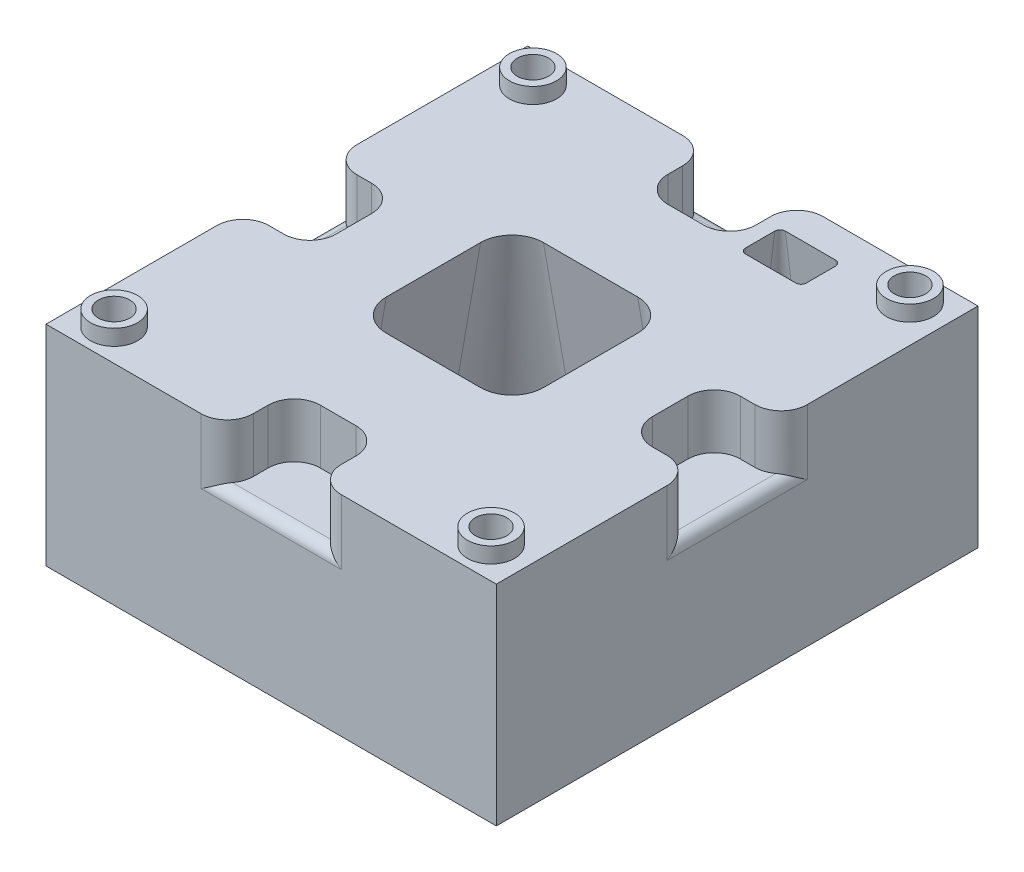
SolidWorks part; units mm, degrees
ref_plane "Plan de face" through (0, 0, 0) normal (0, 0, 1) x (1, 0, 0)
ref_plane "Plan de dessus" through (0, 0, 0) normal (0, 1, 0) x (1, 0, 0)
ref_plane "Plan de droite" through (0, 0, 0) normal (1, 0, 0) x (0, 0, -1)
sketch "Esquisse1" plane through (0, 0, 0) normal (0, 1, 0) x (1, 0, 0)
  line L0 (-19, 4.2) -> (-17.6, 4.2)
  line L1 (-19, 23) -> (-6.7, 23)
  line L2 (-21.5, 20.5) -> (-21.5, 6.7)
  line L3 (-19, -23) -> (-6.7, -23)
  line L4 (21.5, 20.5) -> (21.5, 6.7)
  line L5 (-21.5, 23) -> (21.5, -23) construction
  line L6 (-21.5, -23) -> (21.5, 23) construction
  line L7 (-15.1, 1.7) -> (-15.1, -1.7)
  line L8 (-17.6, -4.2) -> (-19, -4.2)
  line L9 (-4.2, 20.5) -> (-4.2, 19.1)
  line L10 (-1.7, 16.6) -> (1.7, 16.6)
  line L11 (4.2, 19.1) -> (4.2, 20.5)
  line L12 (19, 4.2) -> (17.6, 4.2)
  line L13 (15.1, 1.7) -> (15.1, -1.7)
  line L14 (17.6, -4.2) -> (19, -4.2)
  line L15 (-4.2, -20.5) -> (-4.2, -19.1)
  line L16 (-1.7, -16.6) -> (1.7, -16.6)
  line L17 (4.2, -19.1) -> (4.2, -20.5)
  line L18 (6.7, 23) -> (19, 23)
  line L19 (21.5, -6.7) -> (21.5, -20.5)
  line L20 (6.7, -23) -> (19, -23)
  line L21 (-21.5, -6.7) -> (-21.5, -20.5)
  line L22 (-21.5, -20.5) -> (-21.5, -23)
  line L23 (-21.5, -23) -> (-19, -23)
  line L24 (19, -23) -> (21.5, -23)
  line L25 (21.5, -23) -> (21.5, -20.5)
  line L26 (19, 23) -> (21.5, 23)
  line L27 (21.5, 23) -> (21.5, 20.5)
  line L28 (-19, 23) -> (-21.5, 23)
  line L29 (-21.5, 23) -> (-21.5, 20.5)
  circle A0 centre (-18, 20) radius 1.5
  circle A1 centre (18, 20) radius 1.5
  circle A2 centre (18, -20) radius 1.5
  circle A3 centre (-18, -20) radius 1.5
  arc A4 (19, 4.2) -> (21.5, 6.7) centre (19, 6.7) ccw
  arc A6 (6.7, 23) -> (4.2, 20.5) centre (6.7, 20.5) ccw
  arc A7 (-4.2, 20.5) -> (-6.7, 23) centre (-6.7, 20.5) ccw
  arc A9 (-21.5, 6.7) -> (-19, 4.2) centre (-19, 6.7) ccw
  arc A10 (-19, -4.2) -> (-21.5, -6.7) centre (-19, -6.7) ccw
  arc A12 (-4.2, -20.5) -> (-6.7, -23) centre (-6.7, -20.5) cw
  arc A13 (4.2, -20.5) -> (6.7, -23) centre (6.7, -20.5) ccw
  arc A15 (21.5, -6.7) -> (19, -4.2) centre (19, -6.7) ccw
  arc A16 (4.2, 19.1) -> (1.7, 16.6) centre (1.7, 19.1) cw
  arc A17 (-1.7, 16.6) -> (-4.2, 19.1) centre (-1.7, 19.1) cw
  arc A18 (-17.6, 4.2) -> (-15.1, 1.7) centre (-17.6, 1.7) cw
  arc A19 (-15.1, -1.7) -> (-17.6, -4.2) centre (-17.6, -1.7) cw
  arc A20 (15.1, 1.7) -> (17.6, 4.2) centre (17.6, 1.7) cw
  arc A21 (15.1, -1.7) -> (17.6, -4.2) centre (17.6, -1.7) ccw
  arc A22 (4.2, -19.1) -> (1.7, -16.6) centre (1.7, -19.1) ccw
  arc A23 (-1.7, -16.6) -> (-4.2, -19.1) centre (-1.7, -19.1) ccw
  point P0 (0, 0)
  point P37 (4.2, 23)
  point P40 (-4.2, 23)
  point P46 (-21.5, 4.2)
  point P49 (-21.5, -4.2)
  point P55 (-4.2, -23)
  point P58 (4.2, -23)
  point P64 (21.5, -4.2)
  point P69 (-4.2, 16.6)
  point P72 (-15.1, 4.2)
  point P75 (-15.1, -4.2)
  point P80 (15.1, -4.2)
  point P83 (4.2, -16.6)
  dimension "D3" = 3
  dimension "D4" = 3
  dimension "D5" = 3
  dimension "D6" = 3
  dimension "D21" = 2.5
  dimension "D1" = 46
  dimension "D2" = 43
  dimension "D7" = 36
  dimension "D8" = 36
  dimension "D9" = 17.3
  dimension "D10" = 17.3
  dimension "D11" = 6.4
  dimension "D12" = 18.8
  dimension "D13" = 18.8
  dimension "D14" = 6.4
  dimension "D15" = 6.4
  dimension "D16" = 18.8
  dimension "D17" = 18.8
  dimension "D18" = 17.3
  dimension "D19" = 17.3
  dimension "D20" = 6.4
  dimension "D22" = 3.5
  dimension "D23" = 3
  dimension "D24" = 3.5
  dimension "D25" = 3
extrude "Boss.-Extru.1" add sketch "Esquisse1" along normal blind 20
sketch "Esquisse2" plane through (0, 20, 0) normal (0, 1, 0) x (1, 0, 0)
  circle A0 centre (-18, 20) radius 2.25
  circle A2 centre (18, 20) radius 2.25
  circle A3 centre (18, -20) radius 2.25
  circle A4 centre (-18, -20) radius 2.25
  circle A5 centre (-18, 20) radius 1.5 construction
  circle A6 centre (18, 20) radius 1.5 construction
  circle A7 centre (18, -20) radius 1.5 construction
  circle A8 centre (-18, -20) radius 1.5 construction
  circle A9 centre (-18, 20) radius 1.5
  circle A10 centre (18, 20) radius 1.5
  circle A11 centre (18, -20) radius 1.5
  circle A12 centre (-18, -20) radius 1.5
  dimension "D1" = 4.5
  dimension "D2" = 4.5
  dimension "D3" = 4.5
  dimension "D4" = 4.5
extrude "Boss.-Extru.2" add sketch "Esquisse2" along normal blind 1.5
sketch "Esquisse6" plane through (0, 0, 0) normal (0, -1, 0) x (1, 0, 0)
  line L0 (-21.5, 6.7) -> (-21.5, 23) construction
  line L1 (-21.5, 9.5229) -> (-14.2843, 9.5229)
  line L2 (-21.5, 9.5229) -> (-21.5, -8.8427)
  line L3 (-21.5, -8.8427) -> (-14.2843, -8.8427)
  line L4 (-14.2843, 9.5229) -> (-14.2843, -8.8427)
  line L5 (-21.5, 23) -> (-6.7, 23) construction
  line L6 (-8.3892, 23) -> (7.4067, 23)
  line L7 (-8.3892, 23) -> (-8.3892, 15.8715)
  line L8 (-8.3892, 15.8715) -> (7.4067, 15.8715)
  line L9 (7.4067, 23) -> (7.4067, 15.8715)
  line L10 (21.5, 23) -> (21.5, 6.7) construction
  line L11 (21.5, 11.3368) -> (14.511, 11.3368)
  line L12 (21.5, 11.3368) -> (21.5, -8.8427)
  line L13 (21.5, -8.8427) -> (14.511, -8.8427)
  line L14 (14.511, 11.3368) -> (14.511, -8.8427)
  line L15 (-4.2, -19.1) -> (-4.2, -20.5) construction
  line L16 (-4.2, -19.1) -> (-4.2, -20.5)
  line L17 (-6.7, -23) -> (8.6915, -23)
  line L18 (21.5, -23) -> (6.7, -23) construction
  line L19 (8.6915, -23) -> (8.6915, -16.6)
  line L20 (8.6915, -16.6) -> (-1.7, -16.6)
  arc A0 (-6.7, -23) -> (-4.2, -20.5) centre (-6.7, -20.5) ccw construction
  arc A1 (-1.7, -16.6) -> (-4.2, -19.1) centre (-1.7, -19.1) ccw construction
  arc A2 (-6.7, -23) -> (-4.2, -20.5) centre (-6.7, -20.5) ccw
  arc A3 (-1.7, -16.6) -> (-4.2, -19.1) centre (-1.7, -19.1) ccw
extrude "Boss.-Extru.3" add sketch "Esquisse6" against normal blind 14.8
sketch "Esquisse3" plane through (0, 20, 0) normal (0, 1, 0) x (1, 0, 0)
  line L1 (-4.5, 7.5) -> (4.5, 7.5)
  line L2 (-7.5, 4.5) -> (-7.5, -4.5)
  line L3 (-4.5, -7.5) -> (4.5, -7.5)
  line L4 (7.5, 4.5) -> (7.5, -4.5)
  line L5 (-7.5, 7.5) -> (7.5, -7.5) construction
  line L6 (-7.5, -7.5) -> (7.5, 7.5) construction
  arc A0 (4.5, -7.5) -> (7.5, -4.5) centre (4.5, -4.5) ccw
  arc A1 (-7.5, -4.5) -> (-4.5, -7.5) centre (-4.5, -4.5) ccw
  arc A2 (-4.5, 7.5) -> (-7.5, 4.5) centre (-4.5, 4.5) ccw
  arc A3 (7.5, 4.5) -> (4.5, 7.5) centre (4.5, 4.5) ccw
  point P0 (0, 0)
  dimension "D3" = 3
  dimension "D1" = 15
  dimension "D2" = 15
extrude "Enlèv. mat.-Extru.1" cut sketch "Esquisse3" against normal up to next (20 mm away) draft 10 draft outward yes
sketch "Esquisse4" plane through (0, 20, 0) normal (0, 1, 0) x (1, 0, 0)
  line L1 (6.1, 20) -> (10.9, 20)
  line L2 (5.6, 19.5) -> (5.6, 16.7)
  line L3 (6.1, 16.2) -> (10.9, 16.2)
  line L4 (11.4, 19.5) -> (11.4, 16.7)
  line L5 (5.6, 20) -> (11.4, 16.2) construction
  line L6 (5.6, 16.2) -> (11.4, 20) construction
  line L7 (-6.7, 23) -> (-21.5, 23) construction
  line L8 (21.5, 6.7) -> (21.5, 23) construction
  arc A0 (10.9, 16.2) -> (11.4, 16.7) centre (10.9, 16.7) ccw
  arc A1 (10.9, 20) -> (11.4, 19.5) centre (10.9, 19.5) cw
  arc A2 (6.1, 16.2) -> (5.6, 16.7) centre (6.1, 16.7) cw
  arc A3 (5.6, 19.5) -> (6.1, 20) centre (6.1, 19.5) cw
  point P0 (8.5, 18.1)
  dimension "D5" = 0.5
  dimension "D1" = 13
  dimension "D2" = 4.9
  dimension "D3" = 3.8
  dimension "D4" = 5.8
extrude "Enlèv. mat.-Extru.2" cut sketch "Esquisse4" against normal up to surface (20 mm away) draft 7
sketch "Esquisse5" plane through (0, 0, 0) normal (0, -1, 0) x (1, 0, 0)
  circle A0 centre (-18, 20) radius 2.5
  circle A1 centre (18, 20) radius 2.5
  circle A2 centre (18, -20) radius 2.5
  circle A3 centre (-18, -20) radius 2.5
  circle A4 centre (-18, -20) radius 1.5 construction
  dimension "D1" = 5
  dimension "D2" = 5
  dimension "D3" = 5
  dimension "D4" = 5
extrude "Enlèv. mat.-Extru.3" cut sketch "Esquisse5" against normal blind 18
fillet "Congé4" radius 1 1 edges at (-21.5, 14.8, 0)
fillet "Congé5" radius 1 1 edges at (0, 14.8, 23)
fillet "Congé6" radius 1 1 edges at (21.5, 14.8, 0)
fillet "Congé7" radius 1 1 edges at (0, 14.8, -23)
